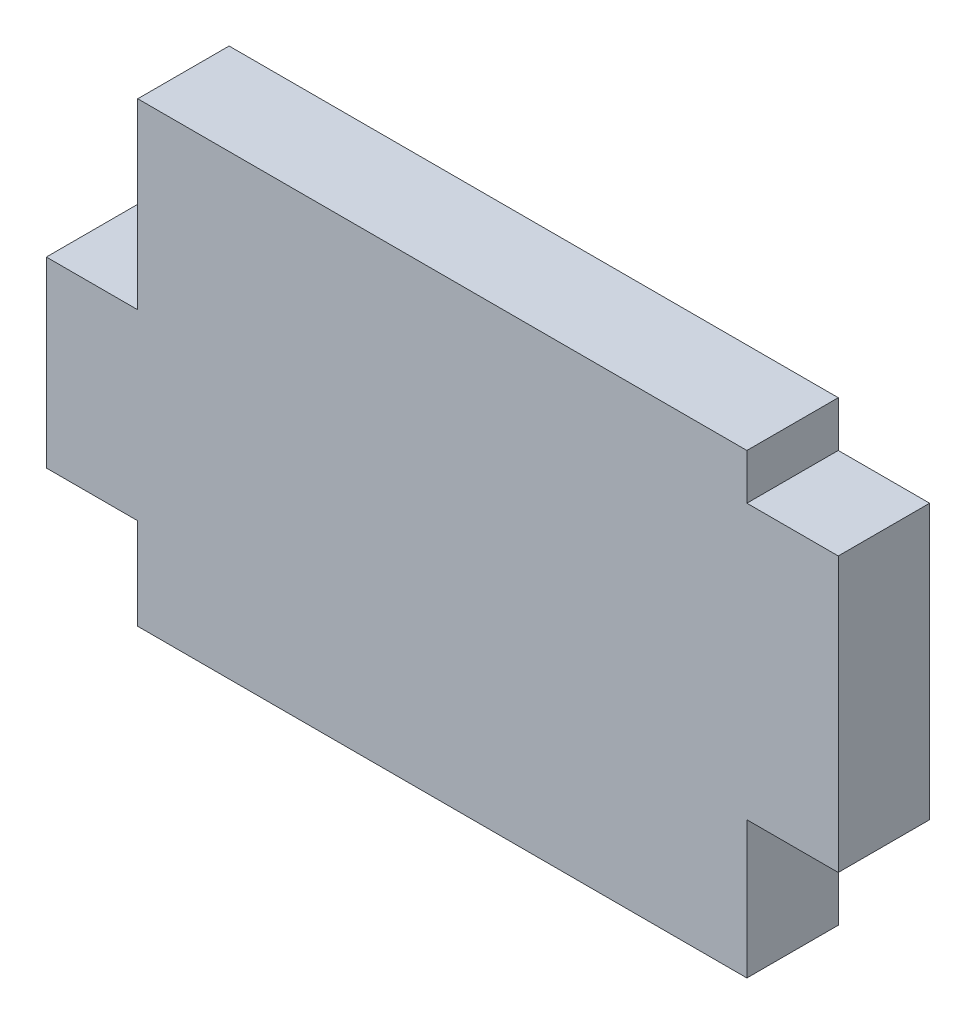
SolidWorks part; units mm, degrees
material "Plywood"
ref_plane "Plan de face" through (0, 0, 0) normal (0, 0, 1) x (1, 0, 0)
ref_plane "Plan de dessus" through (0, 0, 0) normal (0, 1, 0) x (1, 0, 0)
ref_plane "Plan de droite" through (0, 0, 0) normal (1, 0, 0) x (0, 0, -1)
sketch "Esquisse1" plane through (0, 0, 0) normal (0, 0, 1) x (1, 0, 0)
  line L1 (0, 0) -> (52, 0)
  line L2 (0, 0) -> (0, 30)
  line L3 (0, 30) -> (52, 30)
  line L4 (52, 0) -> (52, 30)
  dimension "D1" = 52
  dimension "D2" = 30
extrude "Boss.-Extru.1" add sketch "Esquisse1" along normal blind 6
sketch "Esquisse2" plane through (0, 0, 6) normal (0, 0, 1) x (1, 0, 0)
  line L1 (52, 30) -> (46, 30)
  line L2 (52, 30) -> (52, 27)
  line L3 (52, 27) -> (46, 27)
  line L4 (46, 30) -> (46, 27)
  line L5 (52, 0) -> (46, 0)
  line L6 (52, 0) -> (52, 9)
  line L7 (52, 9) -> (46, 9)
  line L8 (46, 0) -> (46, 9)
  line L9 (0, 30) -> (6, 30)
  line L10 (0, 30) -> (0, 18)
  line L11 (0, 18) -> (6, 18)
  line L12 (6, 30) -> (6, 18)
  line L13 (0, 0) -> (6, 0)
  line L14 (0, 0) -> (0, 6)
  line L15 (0, 6) -> (6, 6)
  line L16 (6, 0) -> (6, 6)
extrude "Enlèv. mat.-Extru.1" cut sketch "Esquisse2" against normal through all
